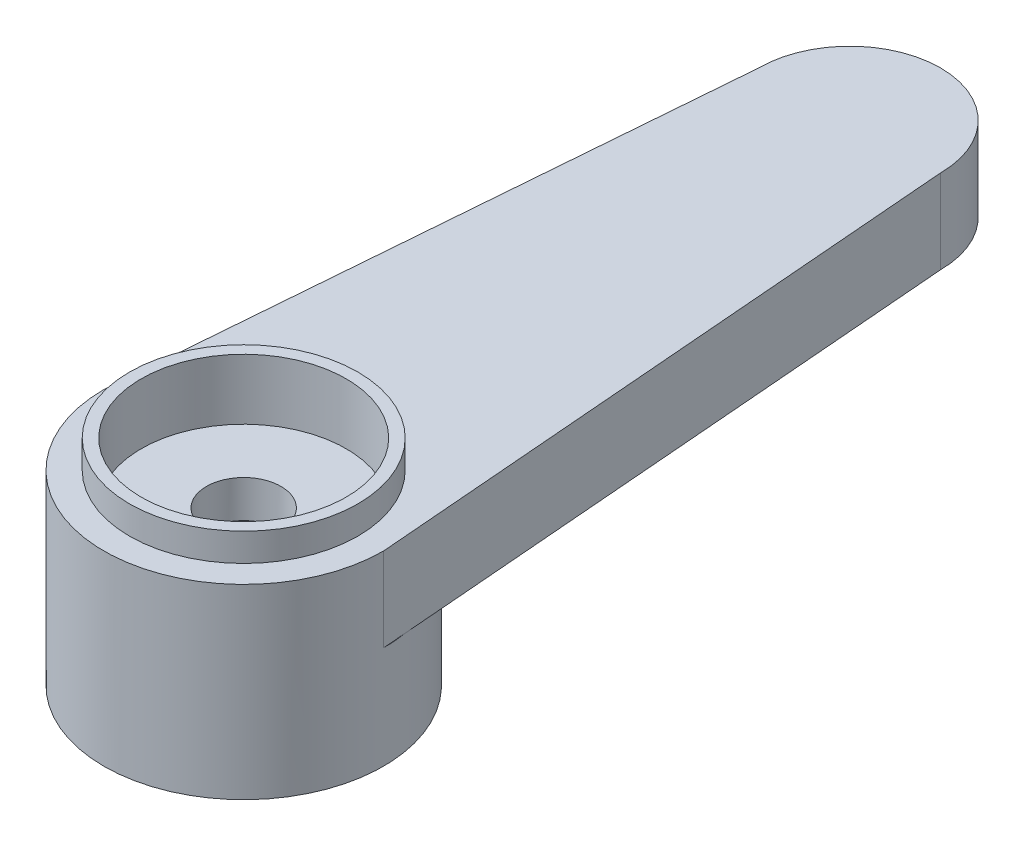
SolidWorks part; units mm, degrees
ref_plane "Front Plane" through (0, 0, 0) normal (0, 0, 1) x (1, 0, 0)
ref_plane "Top Plane" through (0, 0, 0) normal (0, 1, 0) x (1, 0, 0)
ref_plane "Right Plane" through (0, 0, 0) normal (1, 0, 0) x (0, 0, -1)
sketch "Sketch1" plane through (0, 0, 0) normal (0, 1, 0) x (1, 0, 0)
  line L0 (0, 0) -> (0, 13) construction
  line L1 (-3, 0) -> (-1.95, 13)
  line L2 (3, 0) -> (1.95, 13)
  arc A0 (-3, 0) -> (3, 0) centre (0, 0) ccw
  arc A1 (-1.95, 13) -> (1.95, 13) centre (0, 13) cw
  point P7 (0, 14.95)
  dimension "D3" = 1.95
  dimension "D1" = 13
  dimension "D2" = 3
extrude "Boss-Extrude3" add sketch "Sketch1" along normal blind 1.8
sketch "Sketch3" plane through (0, 1.8, 0) normal (0, 1, 0) x (1, 0, 0)
  circle A0 centre (0, 0) radius 2.45
  dimension "D1" = 4.9
extrude "Boss-Extrude4" add sketch "Sketch3" along normal blind 0.6
sketch "Sketch4" plane through (0, 2.4, 0) normal (0, 1, 0) x (1, 0, 0)
  circle A0 centre (0, 0) radius 2.2
  dimension "D1" = 4.4
extrude "Cut-Extrude1" cut sketch "Sketch4" against normal blind 1.3
sketch "Sketch5" plane through (0, 1.1, 0) normal (0, 1, 0) x (1, 0, 0)
  circle A0 centre (0, 0) radius 0.8
  dimension "D1" = 1.6
extrude "Cut-Extrude2" cut sketch "Sketch5" against normal blind 3
sketch "Sketch6" plane through (0, 0, 0) normal (0, -1, 0) x (1, 0, 0)
  circle A0 centre (0, 0) radius 3
extrude "Boss-Extrude5" add sketch "Sketch6" along normal blind 2.2
sketch "Sketch7" plane through (0, -2.2, 0) normal (0, -1, 0) x (1, 0, 0)
  circle A0 centre (0, 0) radius 1.9
  dimension "D1" = 3.8
extrude "Cut-Extrude3" cut sketch "Sketch7" against normal blind 2.5
